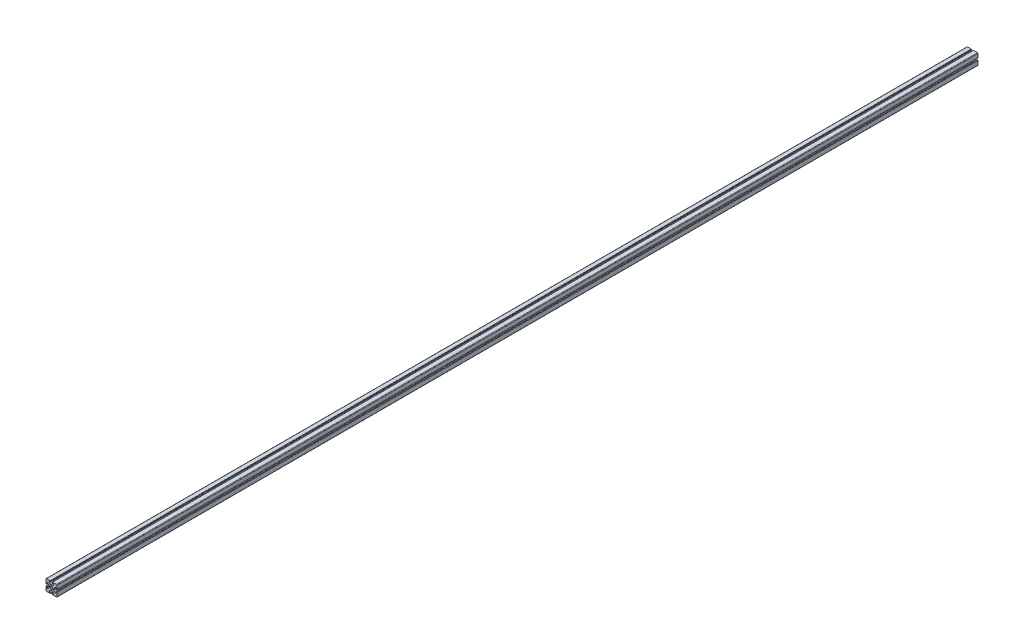
SolidWorks part; units mm, degrees
ref_plane "Front" through (0, 0, 0) normal (0, 0, 1) x (1, 0, 0)
ref_plane "Top" through (0, 0, 0) normal (0, 1, 0) x (1, 0, 0)
ref_plane "Right" through (0, 0, 0) normal (1, 0, 0) x (0, 0, -1)
sketch "草图1" plane through (0, 0, 0) normal (0, 0, 1) x (1, 0, 0)
  line L1 (-20, 20) -> (20, 20)
  line L2 (-20, 20) -> (-20, -20)
  line L3 (-20, -20) -> (20, -20)
  line L4 (20, 20) -> (20, -20)
  line L5 (-20, 20) -> (20, -20) construction
  line L6 (-20, -20) -> (20, 20) construction
  point P0 (0, 0)
  dimension "D1" = 40
extrude "凸台-拉伸1" add sketch "草图1" along normal up to surface (3332.5 mm away)
sketch "草图2" plane through (0, 0, 3332.5) normal (0, 0, 1) x (1, 0, 0)
  circle A0 centre (0, 0) radius 4.05
  dimension "D1" = 8.1
extrude "切除-拉伸1" cut sketch "草图2" against normal blind 10000
sketch "草图4" plane through (0, 0, 3332.5) normal (0, 0, 1) x (1, 0, 0)
  line L0 (20, -20) -> (20, 20) construction
  line L1 (20, 0) -> (20, 4)
  line L2 (20, 0) -> (20, -2.652)
  line L3 (7.8769, 2.6) -> (7.8769, -2.6)
  line L4 (20, 4) -> (16, 4)
  line L5 (20, -2.652) -> (16, -2.652)
  line L6 (16, 10.5) -> (16, 4)
  line L7 (16, 10.5) -> (7.8769, 2.6)
  line L8 (16, -10.5) -> (7.8769, -2.6)
  line L9 (16, -2.652) -> (16, -10.5)
  point P11 (7.8769, 0)
  point P12 (16, 0)
extrude "切除-拉伸2" cut sketch "草图4" against normal blind 10000
fillet "圆角1" radius 1 8 edges at (16, 10.5, 1666.25) (16, -10.5, 1666.25) (7.8769, 2.6, 1666.25) (20, -2.652, 1666.25) (16, -2.652, 1666.25) (20, 4, 1666.25) (16, 4, 1666.25) (7.8769, -2.6, 1666.25)
pattern_circular "阵列(圆周)2" count 4 over 360 about axis through (0, 0, 0) along (0, 0, 1) of "切除-拉伸2"
fillet "圆角2" radius 1 8 edges at (10.5, 16, 1666.25) (-10.5, 16, 1666.25) (-4, 20, 1666.25) (2.652, 16, 1666.25) (2.652, 20, 1666.25) (-2.6, 7.8769, 1666.25) (-4, 16, 1666.25) (2.6, 7.8769, 1666.25)
fillet "圆角3" radius 1 8 edges at (-7.8769, -2.6, 1666.25) (-7.8769, 2.6, 1666.25) (-20, 2.652, 1666.25) (-16, 10.5, 1666.25) (-20, -4, 1666.25) (-16, -4, 1666.25) (-16, -10.5, 1666.25) (-16, 2.652, 1666.25)
fillet "圆角4" radius 1 8 edges at (4, -20, 1666.25) (4, -16, 1666.25) (10.5, -16, 1666.25) (-2.652, -20, 1666.25) (2.6, -7.8769, 1666.25) (-2.6, -7.8769, 1666.25) (-2.652, -16, 1666.25) (-10.5, -16, 1666.25)
fillet "圆角5" radius 2 4 edges at (-20, -20, 1666.25) (20, -20, 1666.25) (-20, 20, 1666.25) (20, 20, 1666.25)
